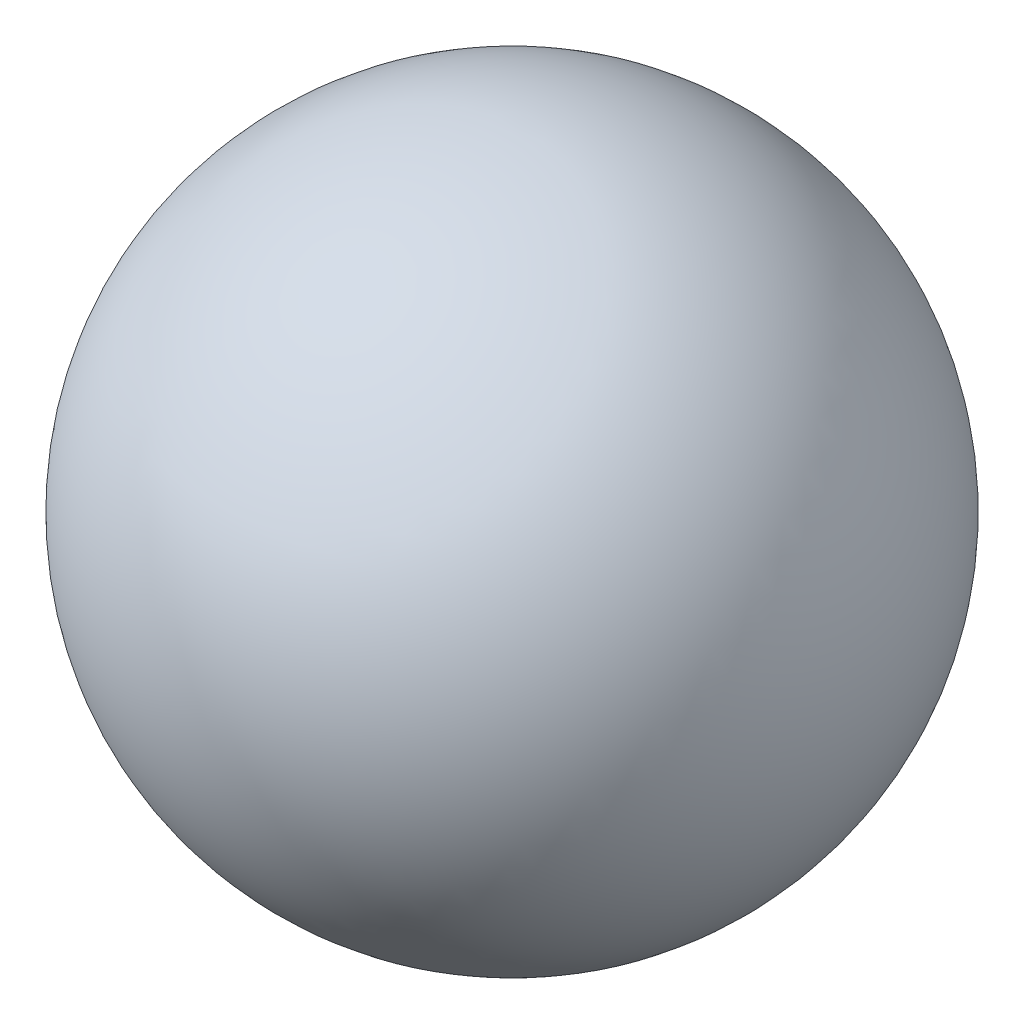
SolidWorks part; units mm, degrees
material "PVC 0.007 塑化"
ref_plane "前基準面" through (0, 0, 0) normal (0, 0, 1) x (1, 0, 0)
ref_plane "上基準面" through (0, 0, 0) normal (0, 1, 0) x (1, 0, 0)
ref_plane "右基準面" through (0, 0, 0) normal (1, 0, 0) x (0, 0, -1)
sketch "草圖1" plane through (0, 0, 0) normal (0, 0, 1) x (1, 0, 0)
  line L0 (0, 35) -> (0, -35)
  arc A0 (0, 35) -> (0, -35) centre (0, 0) cw
  point P6 (0, 0)
  dimension "D1" = 35
revolve "旋轉1" add sketch "草圖1" angle 360 about L0
